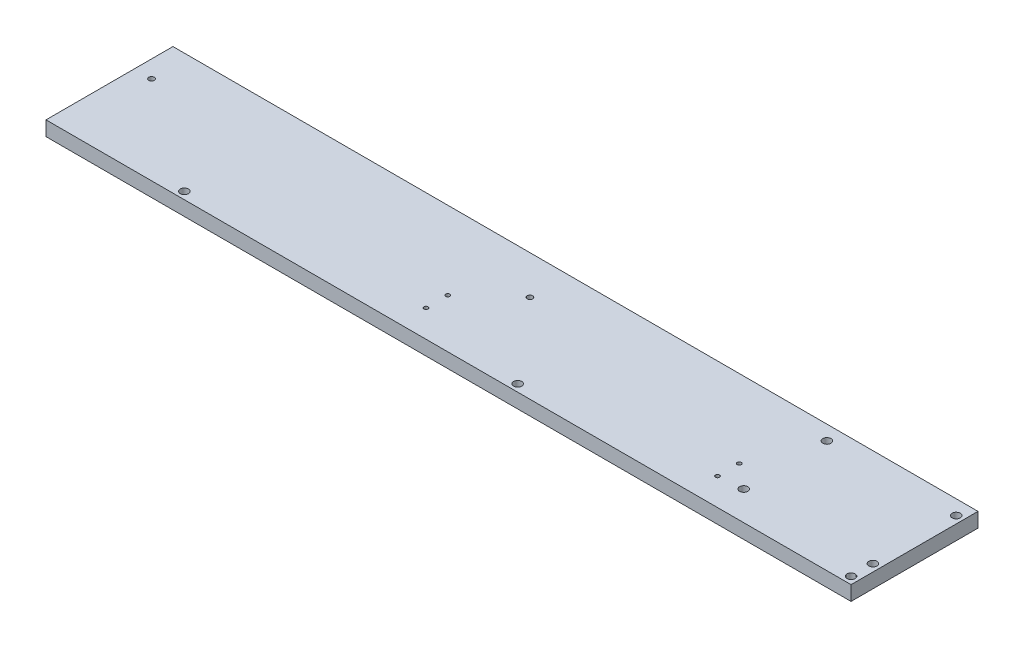
SolidWorks part; units mm, degrees
ref_plane "Front Plane" through (0, 0, 0) normal (0, 0, 1) x (1, 0, 0)
ref_plane "Top Plane" through (0, 0, 0) normal (0, 1, 0) x (1, 0, 0)
ref_plane "Right Plane" through (0, 0, 0) normal (1, 0, 0) x (0, 0, -1)
sketch "Sketch1" plane through (0, 0, 0) normal (0, 1, 0) x (1, 0, 0)
  line B0 (-350.99, 0) -> (0, 0)
  line B1 (0, 0) -> (0, 55.35)
  line B2 (0, 55.35) -> (-350.99, 55.35)
  line B3 (-350.99, 55.35) -> (-350.99, 0)
  circle B4 centre (-293.84, 3.175) radius 1.7859
  circle B5 centre (-197.16, 11.85) radius 0.889
  circle B6 centre (-197.16, 21.35) radius 0.889
  circle B7 centre (-70.1, 21.35) radius 0.889
  circle B8 centre (-70.1, 11.85) radius 0.889
  circle B9 centre (-343.49, 38.5) radius 1.1906
  circle B10 centre (-178.49, 38.5) radius 1.1906
  circle B11 centre (-3.175, 3.175) radius 1.7859
  circle B12 centre (-3.175, 49) radius 1.7859
  circle B13 centre (-3.175, 12.7) radius 1.7859
  circle B14 centre (-148.5075, 3.175) radius 1.7859
  circle B15 centre (-59.525, 49) radius 1.7859
  circle B16 centre (-59.525, 12.7) radius 1.7859
sketch_block_instance "Left_Side_OC-1"
sketch_block "Left_Side_OC" parameters "D2"=3.5719, "D5"=3.5719, "D1"=3.175, "D3"=57.15, "D4"=3.175, "D6"=3.175, "D7"=12.7, "D8"=6.35, "D9"=56.35
extrude "Boss-Extrude1" add sketch "Sketch1" along normal blind 6.35
